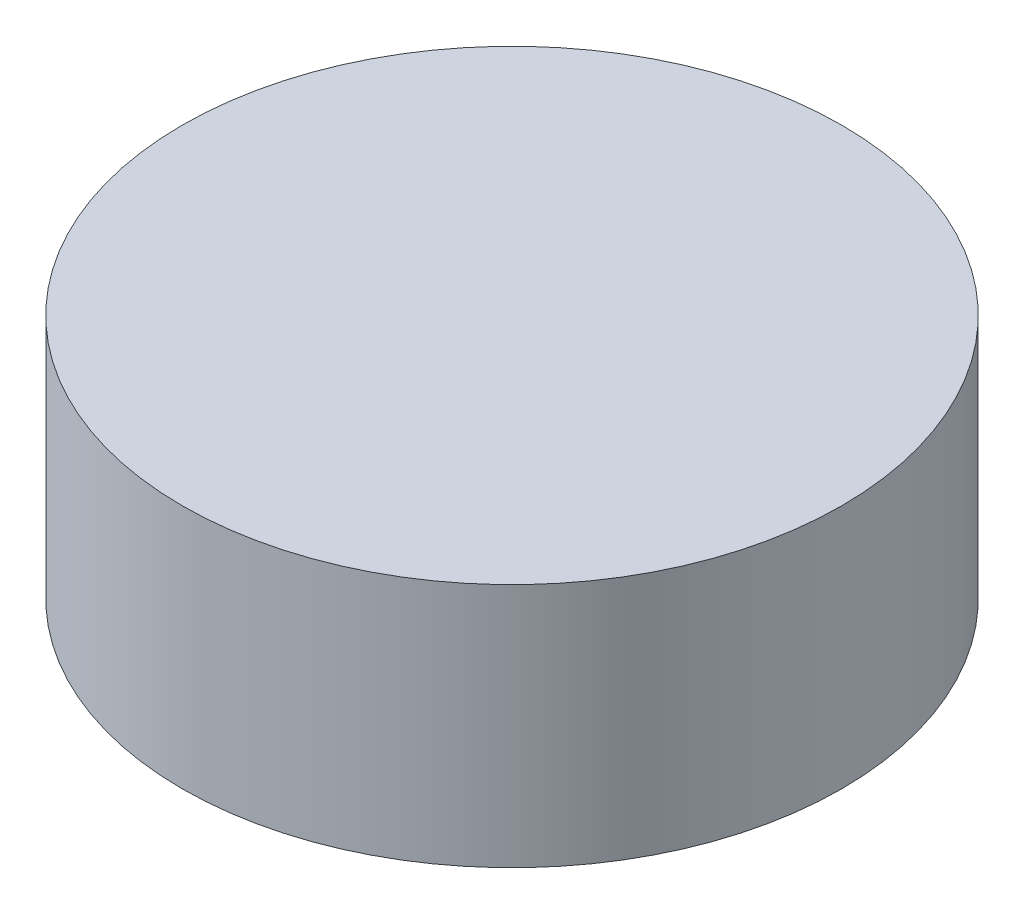
SolidWorks part; units mm, degrees
ref_plane "Front Plane" through (0, 0, 0) normal (0, 0, 1) x (1, 0, 0)
ref_plane "Top Plane" through (0, 0, 0) normal (0, 1, 0) x (1, 0, 0)
ref_plane "Right Plane" through (0, 0, 0) normal (1, 0, 0) x (0, 0, -1)
sketch "Sketch1" plane through (0, 0, 0) normal (0, 0, 1) x (1, 0, 0)
  line L0 (0, 0) -> (0, 3.1) construction
  line L1 (0, 3.1) -> (-3.9, 3.1)
  line L2 (-3.9, 3.1) -> (-3.9, 0.2)
  line L3 (-3.9, 0.2) -> (-3, 0.2)
  line L4 (-3, 0.2) -> (-3, 0)
  line L5 (-3, 0) -> (-2.5, 0)
  line L6 (-2.5, 0) -> (-2.5, 2.1)
  line L7 (-2.5, 2.1) -> (0, 2.1)
  line L8 (0, 2.1) -> (0, 3.1)
  point P3 (-3, 0.1)
  dimension "D1" = 7.8
  dimension "D2" = 5
  dimension "D3" = 6
  dimension "D4" = 0.2
  dimension "D5" = 2.1
  dimension "D6" = 3.1
revolve "Main Body" add sketch "Sketch1" angle 360 about L0
sketch "Sketch2" plane through (0, 2.1, 0) normal (0, -1, 0) x (1, 0, 0)
  line L1 (2.4, -2.4) -> (-2.4, -2.4)
  line L2 (2.4, -2.4) -> (2.4, 2.4)
  line L3 (2.4, 2.4) -> (-2.4, 2.4)
  line L4 (-2.4, -2.4) -> (-2.4, 2.4)
  line L5 (2.4, -2.4) -> (-2.4, 2.4) construction
  line L6 (2.4, 2.4) -> (-2.4, -2.4) construction
  circle A1 centre (0, 0) radius 2.5
  circle A2 centre (0, 0) radius 2.5
  circle M6 centre (0, 0) radius 2.5
  dimension "D2" = 4.8
  dimension "D1" = 0
extrude "Gripping Ribs" add sketch "Sketch2" along normal up to surface (2.1 mm away) contours L3 M6 | L4 M6 | L2 M6 | L1 M6 up to face at (0, 0, -2.5)
